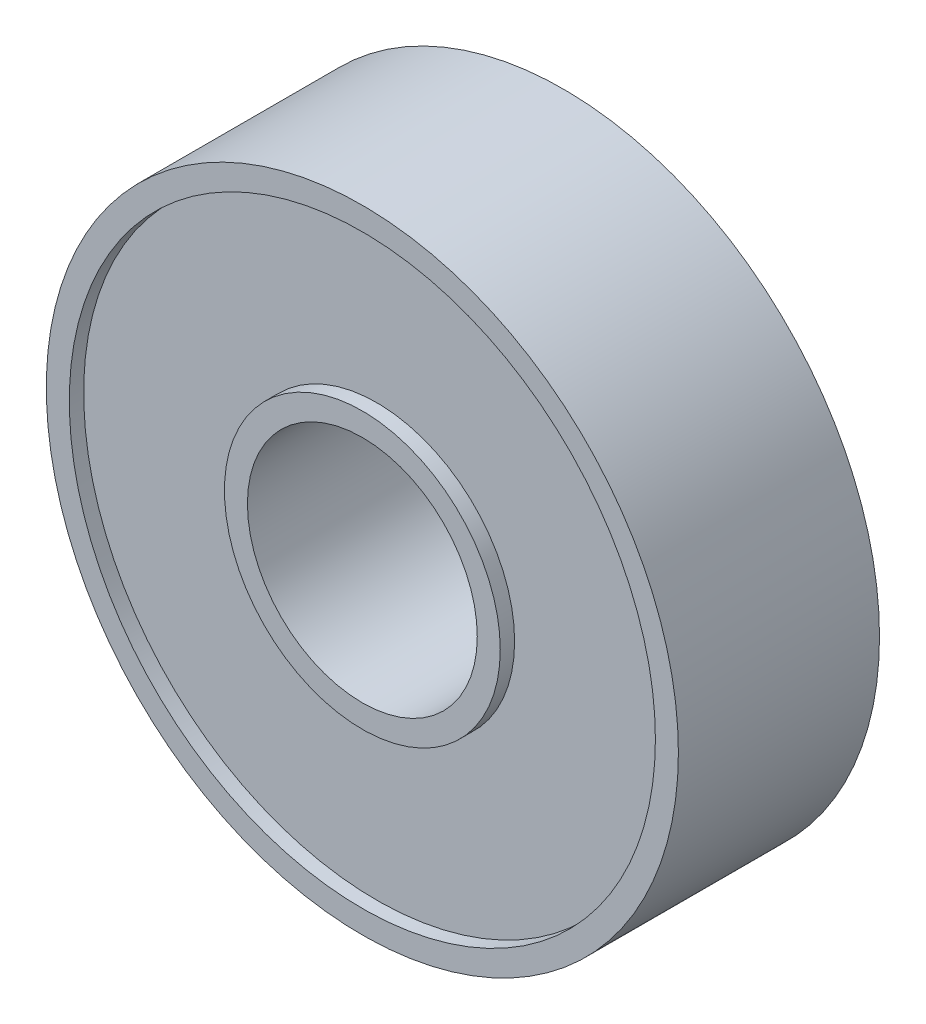
SolidWorks part; units mm, degrees
ref_plane "Top Plane" through (0, 0, 0) normal (0, 0, 1) x (1, 0, 0)
ref_plane "Right Plane" through (0, 0, 0) normal (0, 1, 0) x (1, 0, 0)
ref_plane "Front Plane" through (0, 0, 0) normal (1, 0, 0) x (0, 0, -1)
sketch "Sketch2" plane through (0, 0, 0) normal (1, 0, 0) x (0, 0, -1)
  line L2 (0, 4) -> (-3.5, 4)
  line L3 (-3.5, 4) -> (-3.5, 4.8)
  line L4 (-3.5, 4.8) -> (-3, 4.8)
  line L5 (-3, 4.8) -> (-3, 10.2)
  line L6 (-3, 10.2) -> (-3.5, 10.2)
  line L7 (-3.5, 10.2) -> (-3.5, 11)
  line L8 (-3.5, 11) -> (3.5, 11)
  line L9 (0, 11) -> (0, 0) construction
  line L10 (3.5, 10.2) -> (3.5, 11)
  line L11 (3, 10.2) -> (3.5, 10.2)
  line L12 (3, 4.8) -> (3, 10.2)
  line L13 (3.5, 4.8) -> (3, 4.8)
  line L14 (3.5, 4) -> (3.5, 4.8)
  line L15 (0, 4) -> (3.5, 4)
  line L17 (-4.5381, 0) -> (4.4118, 0) construction
  point P0 (0, 0)
  dimension "D1" = 7
  dimension "D2" = 22
  dimension "D3" = 0.8
  dimension "D4" = 0.5
  dimension "D5" = 8
revolve "Revolve1" add sketch "Sketch2" angle 360 about L17
